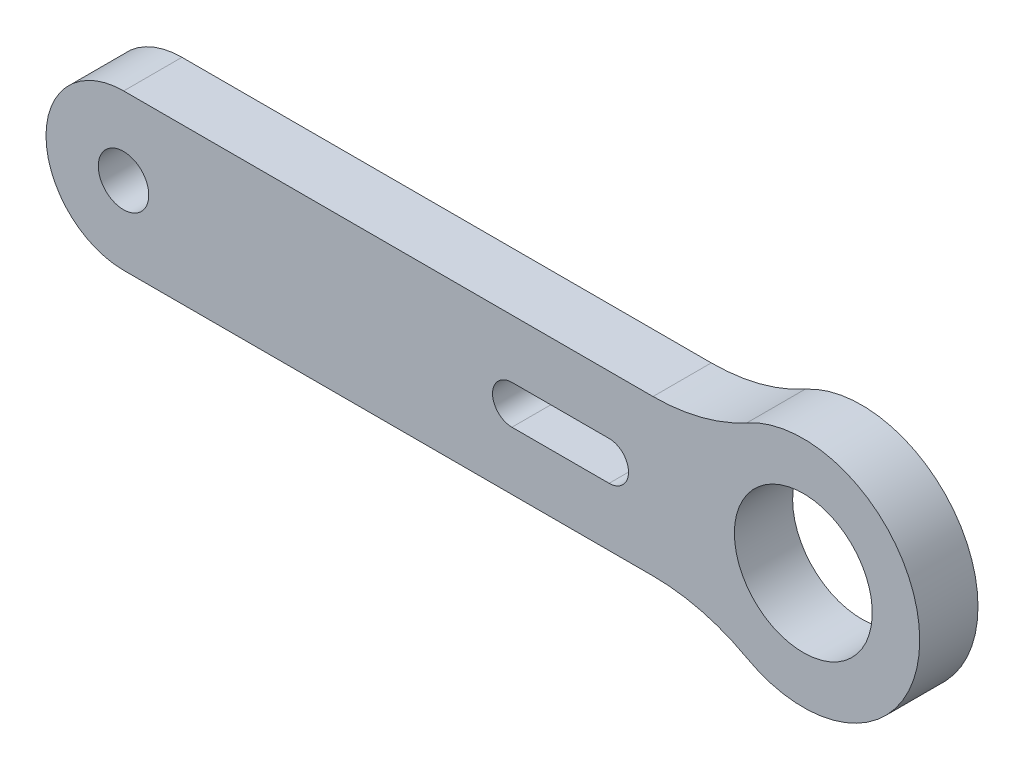
SolidWorks part; units mm, degrees
ref_plane "前视基准面" through (0, 0, 0) normal (0, 0, 1) x (1, 0, 0)
ref_plane "上视基准面" through (0, 0, 0) normal (0, 1, 0) x (1, 0, 0)
ref_plane "右视基准面" through (0, 0, 0) normal (1, 0, 0) x (0, 0, -1)
ref_plane "基准面4" through (0, 0, 3) normal (0, 0, 1) x (1, 0, 0)
sketch "草图1" plane through (0, 0, 3) normal (0, 0, 1) x (1, 0, 0)
  line L0 (15.6408, 8) -> (-11.611, 8)
  line L1 (-11.611, 0) -> (15.6462, 0)
  line L2 (13.3804, 3.0005) -> (8.3788, 3.0005)
  line L3 (8.3788, 5) -> (13.3804, 5)
  circle A0 centre (-11.6194, 4.0002) radius 1.3
  arc A1 (20.4784, 9.248) -> (15.6408, 8) centre (15.6408, 18) cw
  arc A2 (-11.611, 8) -> (-11.611, 0) centre (-11.611, 4) ccw
  arc A3 (15.6462, 0) -> (20.4804, -1.2461) centre (15.6462, -10) cw
  arc A4 (20.4804, -1.2461) -> (20.4784, 9.248) centre (23.3783, 4.0015) ccw
  circle A5 centre (23.3793, 4.0005) radius 3.55
  arc A6 (13.3804, 5) -> (13.3804, 3.0005) centre (13.3804, 4.0003) cw
  arc A7 (8.3788, 3.0005) -> (8.3788, 5) centre (8.3788, 4.0003) cw
extrude "凸台-拉伸1" add sketch "草图1" against normal blind 3
